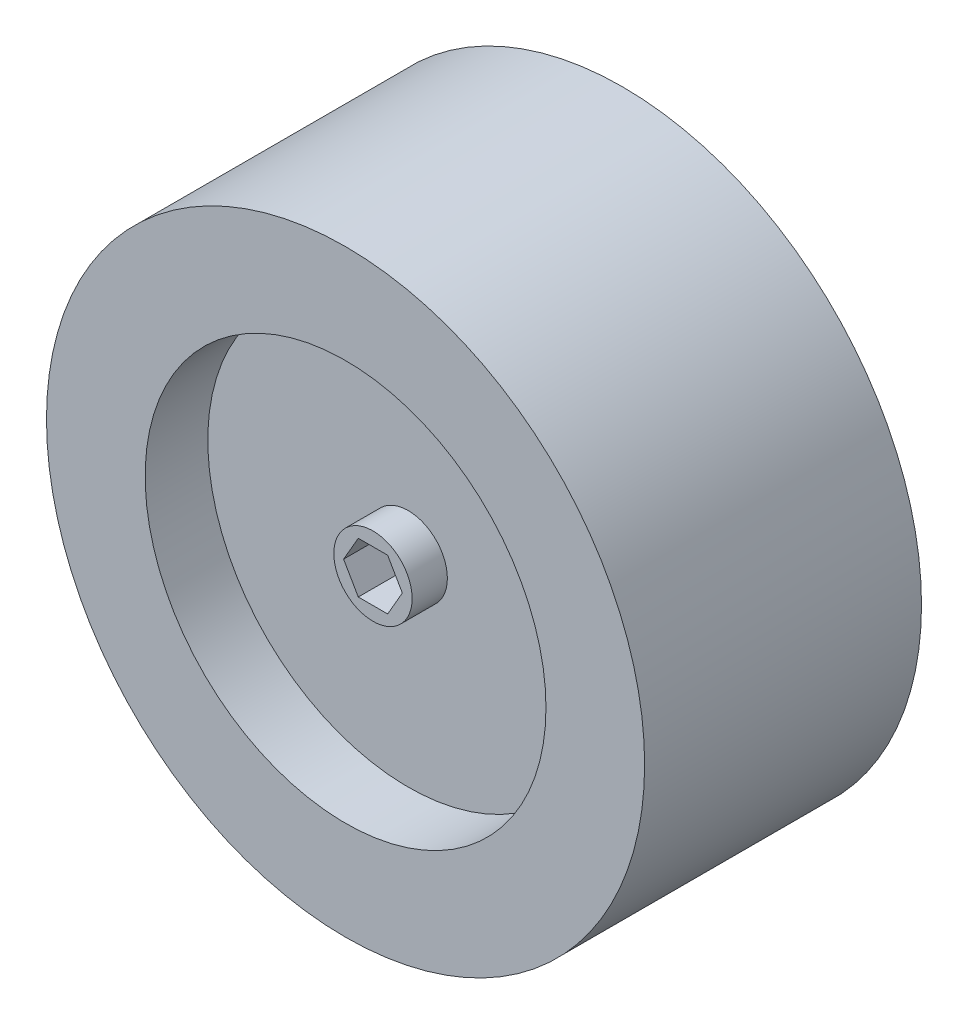
SolidWorks part; units mm, degrees
ref_plane "Front Plane" through (0, 0, 0) normal (0, 0, 1) x (1, 0, 0)
ref_plane "Top Plane" through (0, 0, 0) normal (0, 1, 0) x (1, 0, 0)
ref_plane "Right Plane" through (0, 0, 0) normal (1, 0, 0) x (0, 0, -1)
sketch "Sketch2" plane through (0, 0, 0) normal (0, 0, 1) x (1, 0, 0)
  circle A0 centre (0, 0) radius 48.5
  dimension "D1" = 97
extrude "Boss-Extrude1" add sketch "Sketch2" along normal mid plane 44.9
sketch "Sketch3" plane through (0, 0, 22.45) normal (0, 0, 1) x (1, 0, 0)
  circle A0 centre (0, 0) radius 32.5
  dimension "D1" = 65
extrude "Cut-Extrude1" cut sketch "Sketch3" against normal blind 10.16
sketch "Sketch9" plane through (0, 0, 12.29) normal (0, 0, 1) x (1, 0, 0)
  circle A0 centre (0, 0) radius 6.35
  dimension "D1" = 12.7
extrude "Boss-Extrude2" add sketch "Sketch9" along normal blind 5.715
sketch "Sketch4" plane through (0, 0, 12.29) normal (0, 0, 1) x (1, 0, 0)
  line L1 (2.3816, 4.125) -> (-2.3816, 4.125)
  line L2 (-2.3816, 4.125) -> (-4.7631, 0)
  line L3 (-4.7631, 0) -> (-2.3816, -4.125)
  line L4 (-2.3816, -4.125) -> (2.3816, -4.125)
  line L5 (2.3816, -4.125) -> (4.7631, 0)
  line L6 (4.7631, 0) -> (2.3816, 4.125)
  circle A0 centre (0, 0) radius 4.125 construction
  dimension "D1" = 8.25
extrude "Cut-Extrude2" cut sketch "Sketch4" against normal blind 22.1 and the other way through all
hole_wizard "M5 Clearance Hole1" positions "Sketch6" profile "Sketch7" hole size "M5" standard "ANSI Metric" end condition through all
sketch "Sketch6" plane through (0, 0, -9.81) normal (0, 0, 1) x (1, 0, 0)
  point P0 (0, 0)
sketch "Sketch7" plane through (0, 0, -9.81) normal (1, 0, 0) x (0, -1, 0)
  line L0 (0, 0) -> (0, 12.64)
  line L1 (0, 12.64) -> (2.75, 12.64)
  line L2 (2.75, 12.64) -> (2.75, 0.025)
  line L3 (2.75, 0.025) -> (2.775, 0)
  line L5 (2.775, 0) -> (0, 0)
  line L6 (-2.75, 0.025) -> (-2.775, 0) construction
  line L11 (0, -6.35) -> (0, 107.95) construction
  dimension "Thru Hole Dia." = 5.5
  dimension "Thru Hole Depth" = 12.64
  dimension "Near C'Sink Dia." = 5.55
  dimension "Near C'Sink Angle" = 90
sketch "Sketch8" plane through (0, 0, -22.45) normal (0, 0, -1) x (-1, 0, 0)
  circle A0 centre (0, 0) radius 3.81
  dimension "D1" = 7.62
extrude "Cut-Extrude3" cut sketch "Sketch8" against normal blind 8.255
sketch "Sketch10" plane through (0, 0, -22.45) normal (0, 0, -1) x (-1, 0, 0)
  circle A0 centre (0, 0) radius 25.4
  dimension "D1" = 50.8
extrude "Cut-Extrude4" cut sketch "Sketch10" against normal blind 3.175
